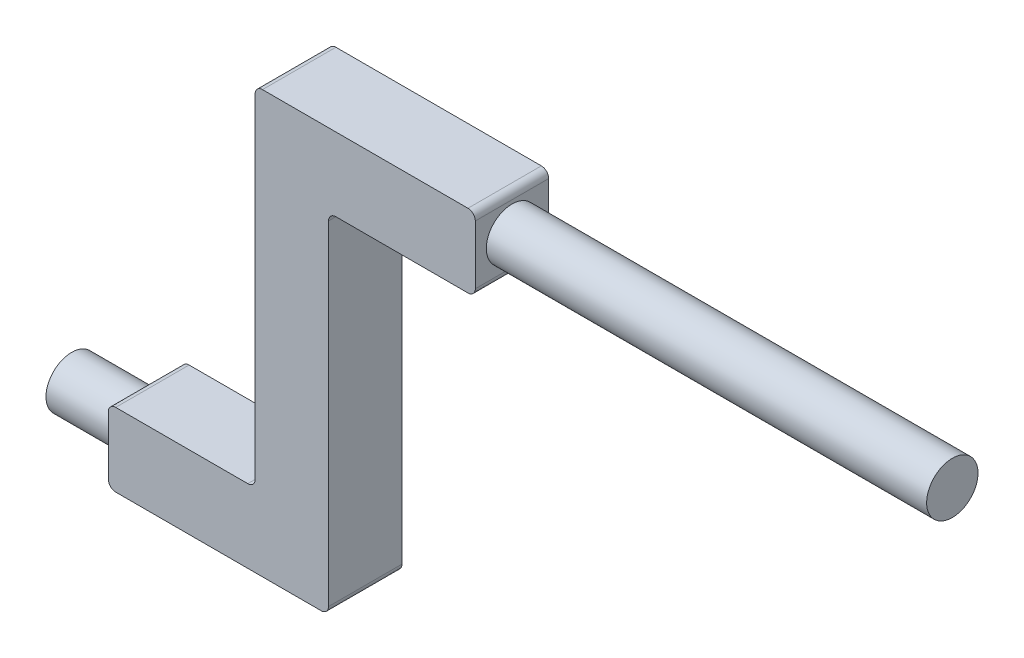
SolidWorks part; units mm, degrees
ref_plane "Front Plane" through (0, 0, 0) normal (0, 0, 1) x (1, 0, 0)
ref_plane "Top Plane" through (0, 0, 0) normal (0, 1, 0) x (1, 0, 0)
ref_plane "Right Plane" through (0, 0, 0) normal (1, 0, 0) x (0, 0, -1)
sketch "Sketch1" plane through (0, 0, 0) normal (0, 0, 1) x (1, 0, 0)
  line L0 (0, 22.75) -> (0, -22.75)
  line L1 (1, 23.75) -> (19, 23.75)
  line L2 (20, 24.75) -> (20, 32.75)
  line L3 (19, 33.75) -> (-9, 33.75)
  line L4 (-10, 32.75) -> (-10, -12.75)
  line L5 (-11, -13.75) -> (-29, -13.75)
  line L6 (-30, -14.75) -> (-30, -22.75)
  line L7 (-29, -23.75) -> (-1, -23.75)
  arc A0 (19, 33.75) -> (20, 32.75) centre (19, 32.75) cw
  arc A1 (20, 24.75) -> (19, 23.75) centre (19, 24.75) cw
  arc A2 (1, 23.75) -> (0, 22.75) centre (1, 22.75) ccw
  arc A3 (0, -22.75) -> (-1, -23.75) centre (-1, -22.75) cw
  arc A4 (-30, -22.75) -> (-29, -23.75) centre (-29, -22.75) ccw
  arc A5 (-30, -14.75) -> (-29, -13.75) centre (-29, -14.75) cw
  arc A6 (-10, -12.75) -> (-11, -13.75) centre (-11, -12.75) cw
  arc A7 (-9, 33.75) -> (-10, 32.75) centre (-9, 32.75) ccw
  point P0 (0, 0)
  point P2 (-30, -18.75)
  point P5 (20, 28.75)
  point P14 (20, 33.75)
  point P17 (20, 23.75)
  point P26 (-30, -13.75)
  point P29 (-10, -13.75)
  dimension "D7" = 1
  dimension "D1" = 10
  dimension "D2" = 52.5
  dimension "D3" = 20
  dimension "D4" = 30
  dimension "D5" = 10
  dimension "D6" = 20
extrude "Boss-Extrude2" add sketch "Sketch1" along normal blind 10
sketch "Sketch3" plane through (20, 0, 0) normal (1, 0, 0) x (0, 0, -1)
  line L0 (-10, 32.75) -> (0, 32.75) construction
  line L1 (-10, 24.75) -> (-10, 32.75) construction
  circle A0 centre (-5, 28.75) radius 3.5
  point P5 (-5, 32.75)
  point P9 (-10, 28.75)
  dimension "D1" = 7
extrude "Boss-Extrude3" add sketch "Sketch3" along normal blind 60
sketch "Sketch4" plane through (-30, 0, 0) normal (-1, 0, 0) x (0, 0, 1)
  line L0 (0, -14.75) -> (0, -22.75) construction
  line L1 (10, -14.75) -> (0, -14.75) construction
  circle A0 centre (5, -18.75) radius 3.5
  point P5 (0, -18.75)
  point P9 (5, -14.75)
  dimension "D1" = 7
extrude "Boss-Extrude4" add sketch "Sketch4" along normal blind 10
